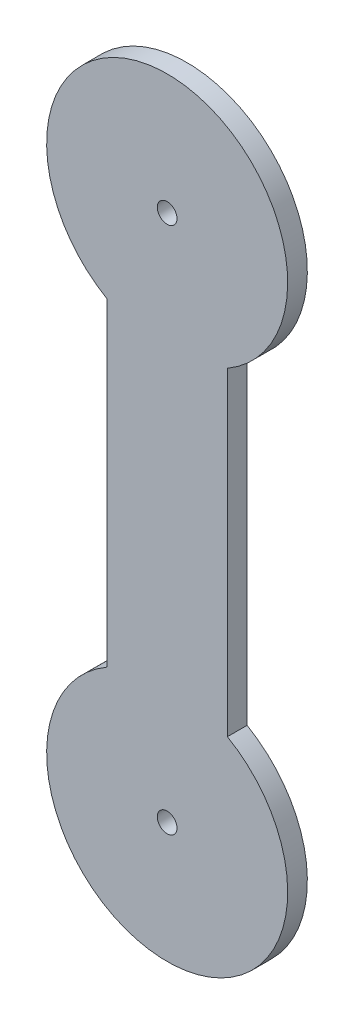
SolidWorks part; units mm, degrees
ref_plane "Front Plane" through (0, 0, 0) normal (0, 0, 1) x (1, 0, 0)
ref_plane "Top Plane" through (0, 0, 0) normal (0, 1, 0) x (1, 0, 0)
ref_plane "Right Plane" through (0, 0, 0) normal (1, 0, 0) x (0, 0, -1)
sketch "Sketch1" plane through (0, 0, 0) normal (0, 0, 1) x (1, 0, 0)
  line L1 (0, 0) -> (38.1, 0)
  line L2 (0, 0) -> (0, 166.878)
  line L3 (0, 166.878) -> (38.1, 166.878)
  line L4 (38.1, 0) -> (38.1, 166.878)
  circle A0 centre (19.05, 0) radius 3.1115
  circle A1 centre (19.05, 166.878) radius 3.1115
  circle A2 centre (19.05, 166.878) radius 38.1
  circle A3 centre (19.05, 0) radius 38.1
  dimension "D3" = 6.223
  dimension "D4" = 6.223
  dimension "D5" = 76.2
  dimension "D6" = 76.2
  dimension "D1" = 166.878
  dimension "D2" = 38.1
extrude "Boss-Extrude1" add sketch "Sketch1" along normal blind 6.223 contours L2 A2 L4 L3 A1 | L4 A2 L2 L3 A1 | A3 L4 A2 L2 | L4 A3 L2 L1 A0 | L2 A3 L4 L1 A0
